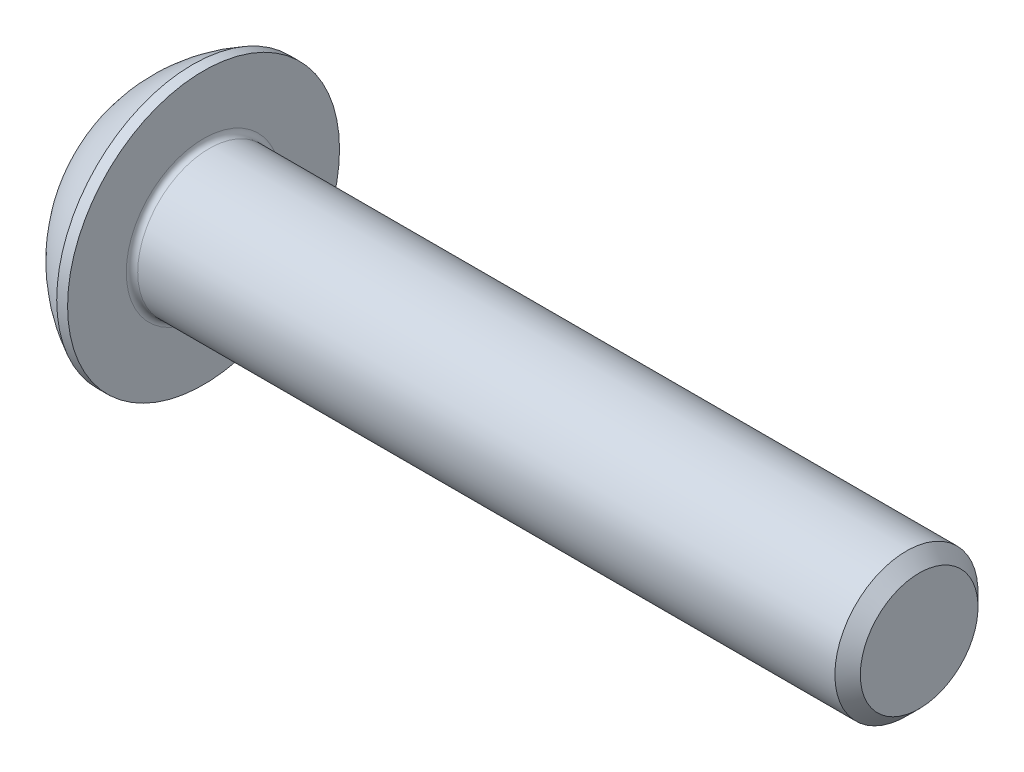
SolidWorks part; units mm, degrees
ref_plane "Plane1" through (0, 0, 0) normal (0, 0, 1) x (1, 0, 0)
ref_plane "Plane2" through (0, 0, 0) normal (0, 1, 0) x (1, 0, 0)
ref_plane "Plane3" through (0, 0, 0) normal (1, 0, 0) x (0, 0, -1)
other "Configuration Table"
sketch "BodySke" plane through (0, 0, 0) normal (0, 0, 1) x (1, 0, 0)
  line L0 (27.75, 0) -> (27.75, 2.055)
  line L1 (27.305, 2.5) -> (2.75, 2.5)
  line L2 (2.75, 2.5) -> (2.75, 4.75)
  line L3 (2.75, 4.75) -> (2.37, 4.75)
  line L4 (0, 0) -> (101.6, 0) construction
  line L5 (2.75, -4.75) -> (2.37, -4.75) construction
  line L6 (55.6768, -2.5) -> (2.75, -2.5) construction
  line L7 (27.75, 0) -> (0, 0)
  line L8 (0, 2.375) -> (0, -2.375) construction
  line L9 (0, 0) -> (0, 2.375)
  line L10 (27.75, 2.055) -> (27.305, 2.5)
  line L11 (27.75, -2.055) -> (27.305, -2.5) construction
  line L12 (3.55, 9.525) -> (3.55, -2.5) construction
  line L13 (2.75, 9.525) -> (2.75, -2.5) construction
  arc A1 (0, 2.375) -> (2.37, 4.75) centre (4.755, 0) cw
  dimension "Head_side_ht" = 0.38
  dimension "Body_ch_ang" = 45
revolve "BaseBody" add sketch "BodySke" angle 360 about L4
cosmetic thread "ThreadCosmetic" [suppressed] parameters "Thread_length"=23.4, "Thread_minor"=4.11
fillet "Fillet1" radius 0.2 1 edges at (2.75, 0, 2.5)
sketch "Sketch2" plane through (0, 0, 0) normal (0, 0, 1) x (1, 0, 0)
  line L0 (0, 1.5) -> (1.56, 1.5)
  line L1 (1.56, 1.5) -> (2.426, 0)
  line L3 (2.426, 0) -> (0, 0)
  line L4 (0, 0) -> (0, 1.5)
  line L5 (0, -1.5) -> (1.56, -1.5) construction
  line L6 (0, 0) -> (47.625, 0) construction
  dimension "D2" = 60
  dimension "PreBroach_depth" = 1.56
  dimension "PreBroach_dia" = 3
revolve "PreBroach" cut sketch "Sketch2" angle 360 about L6
sketch "Sketch3" plane through (0, 0, 0) normal (1, 0, 0) x (0, 0, -1)
  line L0 (-1.5, -0.866) -> (-1.5, 0.866)
  line L1 (-1.5, 0.866) -> (0, 1.7321)
  line L2 (0, 1.7321) -> (1.5, 0.866)
  line L3 (1.5, 0.866) -> (1.5, -0.866)
  line L4 (1.5, -0.866) -> (0, -1.7321)
  line L5 (0, -1.7321) -> (-1.5, -0.866)
  dimension "D1" = 1.5
  dimension "D2" = 1.5
extrude "Hex" cut sketch "Sketch3" along normal blind 1.56
sketch "ThdSchSke" plane through (0, 0, 0) normal (0, 0, 1) x (1, 0, 0)
  line L0 (4.35, -2.055) -> (4.0384, -2.5)
  line L1 (4.35, -2.055) -> (4.6616, -2.5)
  line L2 (4.6616, -2.5) -> (4.6616, -3.125)
  line L3 (-3.175, 0) -> (5.1513, 0) construction
  line L5 (4.6616, -3.125) -> (4.0384, -3.125)
  line L6 (4.0384, -3.125) -> (4.0384, -2.5)
  dimension "SideAngle" = 55
  dimension "VeeAngle" = 70
revolve "ThreadSchematic" [suppressed] cut sketch "ThdSchSke" angle 360 about L3
pattern_linear "ThdSchPat" [suppressed]
equation "\"D1@BodySke\" = \"Head_dia@BodySke\" * .5"
equation "\"Thread_minor@ThreadCosmetic\" = \"Minor_dia@BodySke\""
equation "\"D1@Sketch3\" = \"Hex_size@Sketch3\" / 2"
equation "\"D2@Sketch3\" = \"D1@Sketch3\""
equation "\"D3@Sketch3\" = \"Hex_size@Sketch3\""
equation "\"Thread_length@ThreadCosmetic\" = ((sgn( (\"Length@BodySke\" - \"Advance@BodySke\" * 2.0) - \"Thread_nom@BodySke\" )-1)*( (\"Length@BodySke\" - \"Advance@BodySke\" * 2.0) - \"Thread_nom@BodySke\" ))/-2+ \"Thread_nom@BodySke\""
equation "\"Thread_minor@ThdSchSke\" = \"Minor_dia@BodySke\""
equation "\"Diameter@ThdSchSke\" = \"Diameter@BodySke\""
equation "\"Overcut@ThdSchSke\" = \"Diameter@BodySke\" * 1.25"
equation "\"Start@ThdSchSke\" = \"Head_ht@BodySke\" + \"Length@BodySke\" - \"Thread_length@ThreadCosmetic\"  '---Non-countersunk---"
equation "\"Num_threads@ThdSchPat\" = int( \"Thread_length@ThreadCosmetic\" / \"Advance@BodySke\" + 0.999 )  + 1"
equation "\"Advance@ThdSchPat\" = \"Thread_length@ThreadCosmetic\" /  (\"Num_threads@ThdSchPat\" - 1) 'relax it"
equation "\"Num_threads@ThdSchPat\" = \"Num_threads@ThdSchPat\" - sgn( \"Num_threads@ThdSchPat\" - 1) '---chamfered tips only---"
